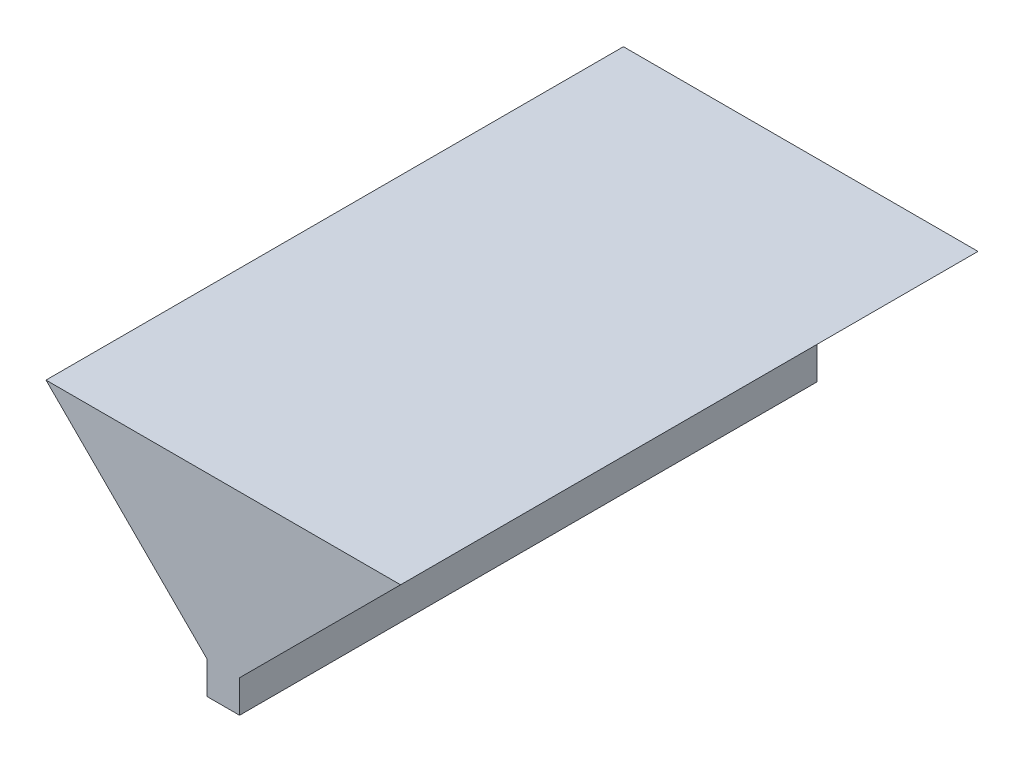
SolidWorks part; units mm, degrees
ref_plane "Front Plane" through (0, 0, 0) normal (0, 0, 1) x (1, 0, 0)
ref_plane "Top Plane" through (0, 0, 0) normal (0, 1, 0) x (1, 0, 0)
ref_plane "Right Plane" through (0, 0, 0) normal (1, 0, 0) x (0, 0, -1)
sketch "Sketch1" plane through (0, 0, 0) normal (0, 0, 1) x (1, 0, 0)
  line L0 (0, 0) -> (0, 2)
  line L1 (0, 0) -> (2, 0)
  line L2 (0, 2) -> (-9.8995, 11.8995)
  line L3 (1, -1.8241) -> (1, 10.4386) construction
  line L4 (2, 0) -> (2, 2)
  line L5 (2, 2) -> (11.8995, 11.8995)
  line L6 (-9.8995, 11.8995) -> (11.8995, 11.8995)
  point P8 (1, 0)
  dimension "D1" = 2
  dimension "D2" = 1
  dimension "D3" = 14
  dimension "D4" = 45
extrude "Boss-Extrude1" add sketch "Sketch1" along normal blind 35.5
